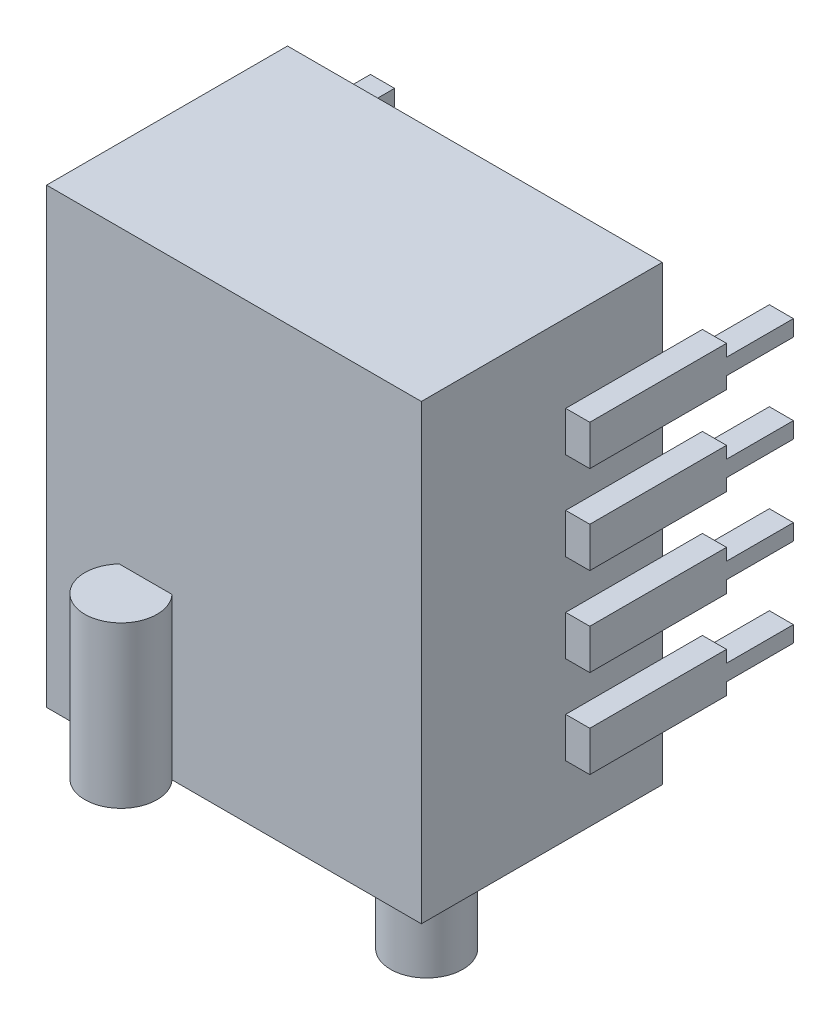
SolidWorks part; units mm, degrees
ref_plane "Face" through (0, 0, 0) normal (0, 0, 1) x (1, 0, 0)
ref_plane "Dessus" through (0, 0, 0) normal (0, 1, 0) x (1, 0, 0)
ref_plane "Droite" through (0, 0, 0) normal (1, 0, 0) x (0, 0, -1)
sketch "Esquisse1" plane through (0, 0, 0) normal (0, 0, 1) x (1, 0, 0)
  line L1 (0, 0) -> (14, 0)
  line L2 (0, 0) -> (0, 16.9)
  line L3 (0, 16.9) -> (14, 16.9)
  line L4 (14, 0) -> (14, 16.9)
  dimension "D1" = 16.9
  dimension "D2" = 14
extrude "Base-Extrusion" add sketch "Esquisse1" along normal blind 9
sketch "Esquisse2" plane through (0, 0, 0) normal (0, -1, 0) x (1, 0, 0)
  line L0 (11.0584, 1.8) -> (4.0521, 1.8) construction
  line L1 (7, 0) -> (7, 4.57) construction
  line L2 (0, 0) -> (14, 0) construction
  circle A0 centre (7, 1.8) radius 1.35
  dimension "D2" = 2.7
  dimension "D1" = 1.8
extrude "Boss.-Extru.1" add sketch "Esquisse2" along normal blind 7.9
sketch "Esquisse3" plane through (0, 0, 0) normal (0, -1, 0) x (1, 0, 0)
  line L0 (3.7, 12.8289) -> (3.7, 7.0138) construction
  line L1 (0, 9) -> (0, 0) construction
  line L2 (6.7577, 9.92) -> (1.5685, 9.92) construction
  circle A0 centre (7, 1.8) radius 1.35 construction
  circle A1 centre (3.7, 9.9214) radius 1.35
  dimension "D2" = 8.12
  dimension "D3" = 2.7
  dimension "D1" = 3.7
extrude "Boss.-Extru.2" add sketch "Esquisse3" against normal blind 6
sketch "Esquisse4" plane through (0, 0, 0) normal (-1, 0, 0) x (0, 0, 1)
  line L0 (3.6075, 13.9806) -> (-1.5, 13.9806)
  line L1 (3.6075, 13.9806) -> (3.6075, 12.4806)
  line L2 (-1.5, 13.9806) -> (-1.5, 13.5306)
  line L3 (3.6075, 12.4806) -> (-1.5, 12.4806)
  line L4 (9, 16.9) -> (9, 0) construction
  line L5 (3.6075, 13.2306) -> (-4.5586, 13.2306) construction
  line L6 (-1.5, 13.5306) -> (-4, 13.5306)
  line L7 (3.6075, 10.6806) -> (-1.5, 10.6806)
  line L8 (-4, 13.5306) -> (-4, 12.9306)
  line L9 (-1.5, 12.9306) -> (-4, 12.9306)
  line L10 (-1.5, 12.9306) -> (-1.5, 12.4806)
  line L11 (3.6075, 10.6806) -> (3.6075, 9.1806)
  line L12 (-1.5, 10.6806) -> (-1.5, 10.2306)
  line L13 (3.6075, 9.1806) -> (-1.5, 9.1806)
  line L14 (-1.5, 10.2306) -> (-4, 10.2306)
  line L15 (-4, 10.2306) -> (-4, 9.6306)
  line L16 (-1.5, 9.6306) -> (-4, 9.6306)
  line L17 (-1.5, 9.6306) -> (-1.5, 9.1806)
  line L18 (3.6075, 7.3806) -> (-1.5, 7.3806)
  line L19 (3.6075, 7.3806) -> (3.6075, 5.8806)
  line L20 (-1.5, 7.3806) -> (-1.5, 6.9306)
  line L21 (3.6075, 5.8806) -> (-1.5, 5.8806)
  line L22 (-1.5, 6.9306) -> (-4, 6.9306)
  line L23 (-4, 6.9306) -> (-4, 6.3306)
  line L24 (-1.5, 6.3306) -> (-4, 6.3306)
  line L25 (-1.5, 6.3306) -> (-1.5, 5.8806)
  line L26 (3.6075, 4.0806) -> (-1.5, 4.0806)
  line L27 (3.6075, 4.0806) -> (3.6075, 2.5806)
  line L28 (-1.5, 4.0806) -> (-1.5, 3.6306)
  line L29 (3.6075, 2.5806) -> (-1.5, 2.5806)
  line L30 (-1.5, 3.6306) -> (-4, 3.6306)
  line L31 (-4, 3.6306) -> (-4, 3.0306)
  line L32 (-1.5, 3.0306) -> (-4, 3.0306)
  line L33 (-1.5, 3.0306) -> (-1.5, 2.5806)
  dimension "D1" = 1.5
  dimension "D2" = 10.5
  dimension "D3" = 0.6
  dimension "D4" = 2.5
extrude "Extrusion1" add sketch "Esquisse4" along normal blind 0.9
sketch "Esquisse5" plane through (14, 0, 0) normal (1, 0, 0) x (0, 0, -1)
  line L8 (1.5, 13.9806) -> (-3.6075, 13.9806)
  line L9 (1.5, 13.5306) -> (1.5, 13.9806)
  line L10 (4, 13.5306) -> (1.5, 13.5306)
  line L11 (4, 12.9306) -> (4, 13.5306)
  line L12 (1.5, 12.9306) -> (4, 12.9306)
  line L13 (1.5, 12.4806) -> (1.5, 12.9306)
  line L14 (-3.6075, 12.4806) -> (1.5, 12.4806)
  line L15 (-3.6075, 13.9806) -> (-3.6075, 12.4806)
  line L16 (1.5, 13.9806) -> (-3.6075, 13.9806)
  line L17 (1.5, 13.5306) -> (1.5, 13.9806)
  line L18 (4, 13.5306) -> (1.5, 13.5306)
  line L19 (4, 12.9306) -> (4, 13.5306)
  line L20 (1.5, 12.9306) -> (4, 12.9306)
  line L21 (1.5, 12.4806) -> (1.5, 12.9306)
  line L22 (-3.6075, 12.4806) -> (1.5, 12.4806)
  line L23 (-3.6075, 13.9806) -> (-3.6075, 12.4806)
  line L24 (1.5, 7.3806) -> (-3.6075, 7.3806)
  line L25 (1.5, 6.9306) -> (1.5, 7.3806)
  line L26 (4, 6.9306) -> (1.5, 6.9306)
  line L27 (4, 6.3306) -> (4, 6.9306)
  line L28 (1.5, 6.3306) -> (4, 6.3306)
  line L29 (1.5, 5.8806) -> (1.5, 6.3306)
  line L30 (-3.6075, 5.8806) -> (1.5, 5.8806)
  line L31 (-3.6075, 7.3806) -> (-3.6075, 5.8806)
  line L32 (1.5, 7.3806) -> (-3.6075, 7.3806)
  line L33 (1.5, 6.9306) -> (1.5, 7.3806)
  line L34 (4, 6.9306) -> (1.5, 6.9306)
  line L35 (4, 6.3306) -> (4, 6.9306)
  line L36 (1.5, 6.3306) -> (4, 6.3306)
  line L37 (1.5, 5.8806) -> (1.5, 6.3306)
  line L38 (-3.6075, 5.8806) -> (1.5, 5.8806)
  line L39 (-3.6075, 7.3806) -> (-3.6075, 5.8806)
  line L40 (-3.6075, 10.6806) -> (-3.6075, 9.1806)
  line L41 (1.5, 10.6806) -> (-3.6075, 10.6806)
  line L42 (1.5, 10.2306) -> (1.5, 10.6806)
  line L43 (4, 10.2306) -> (1.5, 10.2306)
  line L44 (4, 9.6306) -> (4, 10.2306)
  line L45 (1.5, 9.6306) -> (4, 9.6306)
  line L46 (1.5, 9.1806) -> (1.5, 9.6306)
  line L47 (-3.6075, 9.1806) -> (1.5, 9.1806)
  line L48 (-3.6075, 10.6806) -> (-3.6075, 9.1806)
  line L49 (1.5, 10.6806) -> (-3.6075, 10.6806)
  line L50 (1.5, 10.2306) -> (1.5, 10.6806)
  line L51 (4, 10.2306) -> (1.5, 10.2306)
  line L52 (4, 9.6306) -> (4, 10.2306)
  line L53 (1.5, 9.6306) -> (4, 9.6306)
  line L54 (1.5, 9.1806) -> (1.5, 9.6306)
  line L55 (-3.6075, 9.1806) -> (1.5, 9.1806)
  line L56 (-3.6075, 4.0806) -> (-3.6075, 2.5806)
  line L57 (1.5, 4.0806) -> (-3.6075, 4.0806)
  line L58 (1.5, 3.6306) -> (1.5, 4.0806)
  line L59 (4, 3.6306) -> (1.5, 3.6306)
  line L60 (4, 3.0306) -> (4, 3.6306)
  line L61 (1.5, 3.0306) -> (4, 3.0306)
  line L62 (1.5, 2.5806) -> (1.5, 3.0306)
  line L63 (-3.6075, 2.5806) -> (1.5, 2.5806)
  line L64 (-3.6075, 4.0806) -> (-3.6075, 2.5806)
  line L65 (1.5, 4.0806) -> (-3.6075, 4.0806)
  line L66 (1.5, 3.6306) -> (1.5, 4.0806)
  line L67 (4, 3.6306) -> (1.5, 3.6306)
  line L68 (4, 3.0306) -> (4, 3.6306)
  line L69 (1.5, 3.0306) -> (4, 3.0306)
  line L70 (1.5, 2.5806) -> (1.5, 3.0306)
  line L71 (-3.6075, 2.5806) -> (1.5, 2.5806)
  dimension "D1" = 0
  dimension "D2" = 0
  dimension "D3" = 0
  dimension "D4" = 0
extrude "Extrusion2" add sketch "Esquisse5" along normal blind 0.9
